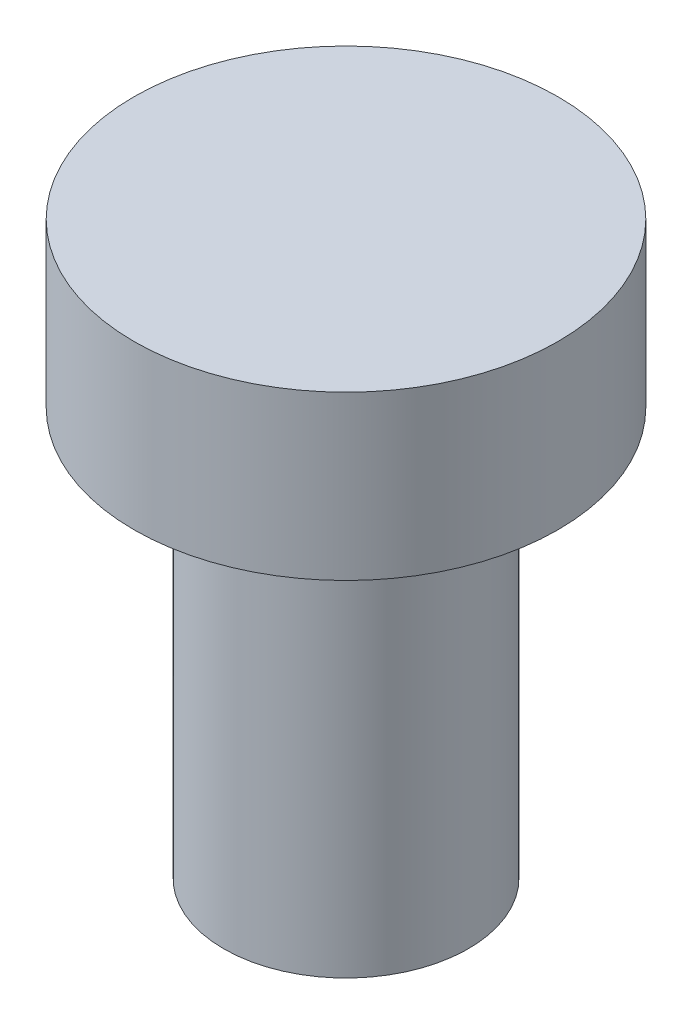
SolidWorks part; units mm, degrees
ref_plane "Front Plane" through (0, 0, 0) normal (0, 0, 1) x (1, 0, 0)
ref_plane "Top Plane" through (0, 0, 0) normal (0, 1, 0) x (1, 0, 0)
ref_plane "Right Plane" through (0, 0, 0) normal (1, 0, 0) x (0, 0, -1)
sketch "Sketch1" plane through (0, 0, 0) normal (0, 1, 0) x (1, 0, 0)
  circle A0 centre (0, 0) radius 1.5
extrude "Boss-Extrude1" add sketch "Sketch1" along normal blind 5
sketch "Sketch3" plane through (0, 5, 0) normal (0, 1, 0) x (1, 0, 0)
  circle A0 centre (0, 0) radius 2.6
extrude "Boss-Extrude2" add sketch "Sketch3" along normal blind 2
